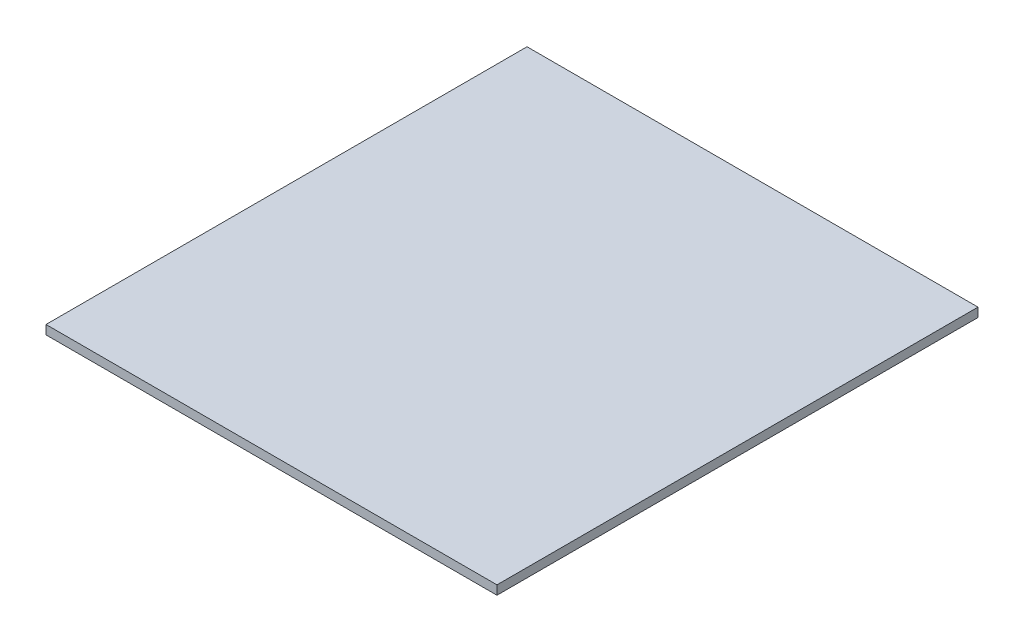
SolidWorks part; units mm, degrees
ref_plane "Front Plane" through (0, 0, 0) normal (0, 0, 1) x (1, 0, 0)
ref_plane "Top Plane" through (0, 0, 0) normal (0, 1, 0) x (1, 0, 0)
ref_plane "Right Plane" through (0, 0, 0) normal (1, 0, 0) x (0, 0, -1)
sketch "Sketch1" plane through (0, 0, 0) normal (0, 1, 0) x (1, 0, 0)
  line L1 (-75, -80) -> (75, -80)
  line L2 (-75, -80) -> (-75, 80)
  line L3 (-75, 80) -> (75, 80)
  line L4 (75, -80) -> (75, 80)
  line L5 (-75, -80) -> (75, 80) construction
  line L6 (-75, 80) -> (75, -80) construction
  point P0 (0, 0)
  dimension "D1" = 150
  dimension "D2" = 160
extrude "Boss-Extrude1" add sketch "Sketch1" along normal blind 3
